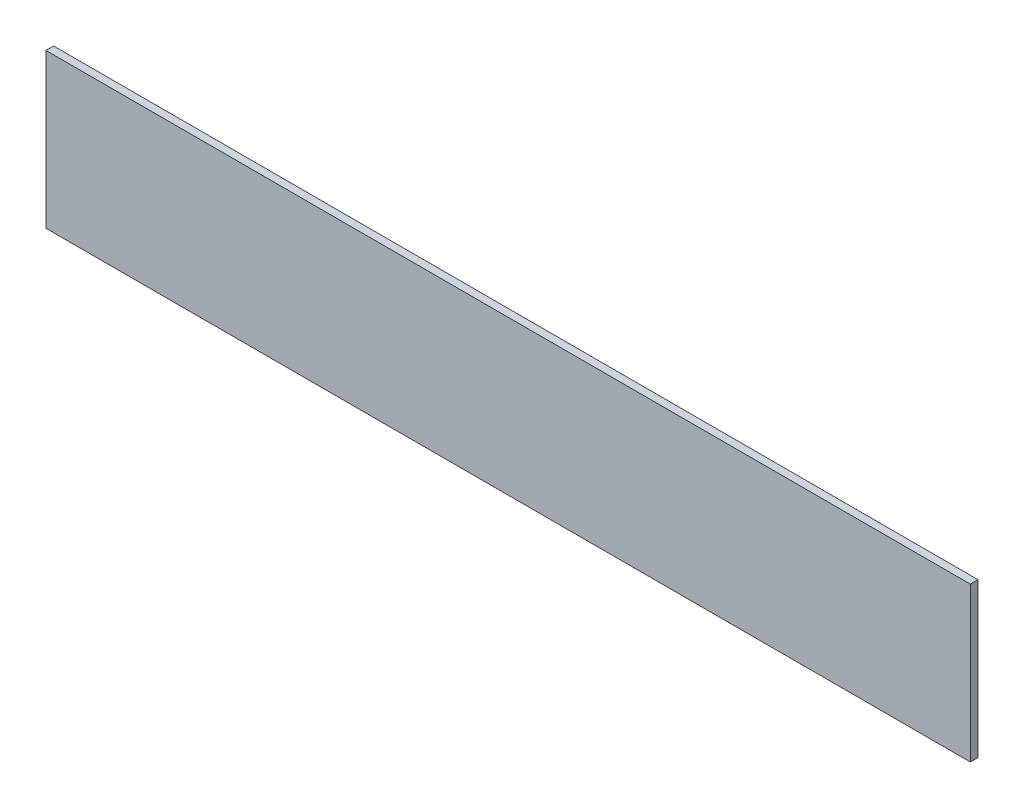
SolidWorks part; units mm, degrees
ref_plane "Plan de face" through (0, 0, 0) normal (0, 0, 1) x (1, 0, 0)
ref_plane "Plan de dessus" through (0, 0, 0) normal (0, 1, 0) x (1, 0, 0)
ref_plane "Plan de droite" through (0, 0, 0) normal (1, 0, 0) x (0, 0, -1)
sketch "Esquisse1" plane through (0, 0, 0) normal (0, 0, 1) x (1, 0, 0)
  line L1 (0, 0) -> (1200, 0)
  line L2 (0, 0) -> (0, -200)
  line L3 (0, -200) -> (1200, -200)
  line L4 (1200, 0) -> (1200, -200)
  dimension "D1" = 200
  dimension "D2" = 1200
extrude "Boss.-Extru.1" add sketch "Esquisse1" along normal blind 10
